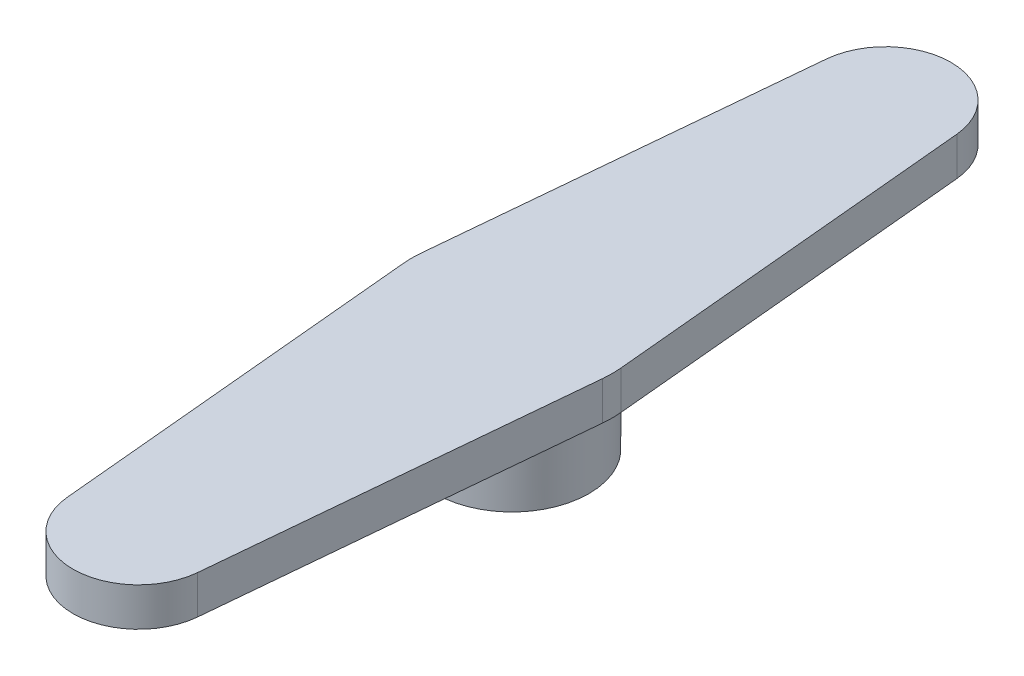
SolidWorks part; units mm, degrees
ref_plane "정면" through (0, 0, 0) normal (0, 0, 1) x (1, 0, 0)
ref_plane "윗면" through (0, 0, 0) normal (0, 1, 0) x (1, 0, 0)
ref_plane "우측면" through (0, 0, 0) normal (1, 0, 0) x (0, 0, -1)
sketch "스케치1" plane through (0, 0, 0) normal (0, 1, 0) x (1, 0, 0)
  line L0 (0, -24.25) -> (0, 0) construction
  line L1 (0, 0) -> (0, 24.25) construction
  line L2 (-4.2317, 24.6443) -> (-6.472, 0.6031)
  line L3 (-6.472, -0.6031) -> (-4.2317, -24.6443)
  line L4 (6.472, -0.6031) -> (4.2317, -24.6443)
  line L5 (6.472, 0.6031) -> (4.2317, 24.6443)
  circle A0 centre (0, 0) radius 6.5
  circle A1 centre (0, -24.25) radius 4.25
  circle A2 centre (0, 24.25) radius 4.25
  point P15 (0, 28.5)
  point P16 (0, -28.5)
  dimension "D1" = 13
  dimension "D2" = 8.5
  dimension "D3" = 57
extrude "보스-돌출1" add sketch "스케치1" along normal blind 2.5 contours A2 L2 A0 L5 | A2 | A0 | A1 L4 A0 L3 | A1
sketch "스케치2" plane through (0, 0, 0) normal (0, -1, 0) x (1, 0, 0)
  circle A0 centre (0, 0) radius 3.5
  circle A1 centre (0, 0) radius 5
  dimension "D1" = 7
  dimension "D2" = 10
extrude "보스-돌출2" add sketch "스케치2" along normal blind 5
